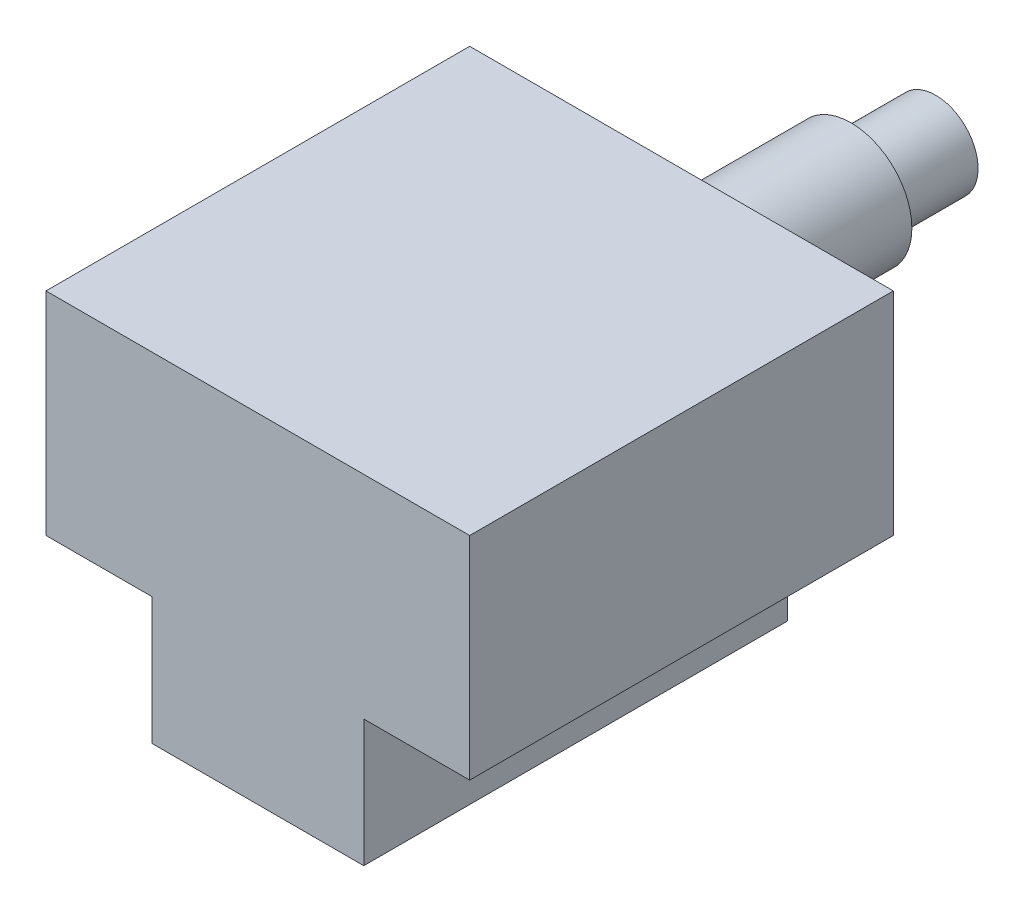
SolidWorks part; units mm, degrees
material "可锻铸铁"
ref_plane "前视基准面" through (0, 0, 0) normal (0, 0, 1) x (1, 0, 0)
ref_plane "上视基准面" through (0, 0, 0) normal (0, 1, 0) x (1, 0, 0)
ref_plane "右视基准面" through (0, 0, 0) normal (1, 0, 0) x (0, 0, -1)
sketch "草图1" plane through (0, 0, 0) normal (0, 0, 1) x (1, 0, 0)
  line L0 (0, 0) -> (0, -115.9258) construction
  line L1 (-50, 25) -> (50, 25)
  line L2 (-50, 25) -> (-50, -25)
  line L3 (-50, -25) -> (50, -25)
  line L4 (50, 25) -> (50, -25)
  line L5 (-50, 25) -> (50, -25) construction
  line L6 (-50, -25) -> (50, 25) construction
  line L8 (-25, -55) -> (25, -55)
  line L9 (-25, -55) -> (-25, -25)
  line L10 (-25, -25) -> (25, -25)
  line L11 (25, -55) -> (25, -25)
  line L12 (-25, -55) -> (25, -25) construction
  line L13 (-25, -25) -> (25, -55) construction
  line L14 (-50, -105) -> (50, -105)
  line L15 (-50, -105) -> (-50, -55)
  line L16 (-50, -55) -> (50, -55)
  line L17 (50, -105) -> (50, -55)
  line L18 (-50, -105) -> (50, -55) construction
  line L19 (-50, -55) -> (50, -105) construction
  point P0 (0, 0)
  point P8 (0, -40)
  point P13 (0, -80)
  dimension "D1" = 100
  dimension "D2" = 50
  dimension "D3" = 30
  dimension "D4" = 50
extrude "凸台-拉伸1" add sketch "草图1" along normal mid plane 100 contours L4 L1 L2 L3 | L8 L11 L3 L9 | L14 L17 L16 L8 L15
sketch "草图2" plane through (0, 0, -50) normal (0, 0, -1) x (-1, 0, 0)
  circle A0 centre (0, 0) radius 14.3732
extrude "凸台-拉伸2" add sketch "草图2" along normal blind 30
sketch "草图3" plane through (0, 0, 50) normal (0, 0, 1) x (1, 0, 0)
  line L0 (0, 25) -> (0, -105) construction
  line L1 (-50, 25) -> (50, 25) construction
  line L2 (-50, -105) -> (50, -105) construction
  line L3 (-50, 25) -> (0, -105) construction
  line L5 (0, -105) -> (50, -105)
  line L6 (50, -105) -> (50, 25)
  line L7 (25.7766, 25) -> (0, -105)
  line L8 (50, -105) -> (50, 25)
  line L9 (25.7766, 25) -> (50, 25)
  line M3 (50, -25) -> (50, 25)
  line M4 (50, 25) -> (-50, 25)
  line M10 (-50, -105) -> (50, -105)
  line M11 (50, -105) -> (50, -55)
  line M12 (50, -55) -> (25, -55)
  line M13 (25, -55) -> (25, -25)
  line M14 (25, -25) -> (50, -25)
extrude "切除-拉伸1" [suppressed] cut sketch "草图3" against normal blind 196 contours L7 M4 M10 M11 M12 M13 M14 M3
mirror "镜向1" [suppressed] about plane through (0, 0, 0) normal (1, 0, 0)
sketch "草图4" plane through (0, 0, -50) normal (0, 0, -1) x (-1, 0, 0)
  line L1 (-50, -55) -> (50, -55)
  line L2 (-50, -55) -> (-50, -105)
  line L3 (-50, -105) -> (50, -105)
  line L4 (50, -55) -> (50, -105)
extrude "切除-拉伸2" cut sketch "草图4" against normal through all both and the other way through all
sketch "草图5" plane through (0, 0, -80) normal (0, 0, -1) x (-1, 0, 0)
  circle A0 centre (0, 0) radius 10
  dimension "D1" = 20
extrude "凸台-拉伸3" add sketch "草图5" along normal blind 30
sketch "草图6" plane through (0, 0, -80) normal (0, 0, -1) x (-1, 0, 0)
  circle A0 centre (0, 0) radius 14.3732
extrude "凸台-拉伸4" add sketch "草图6" along normal blind 10
